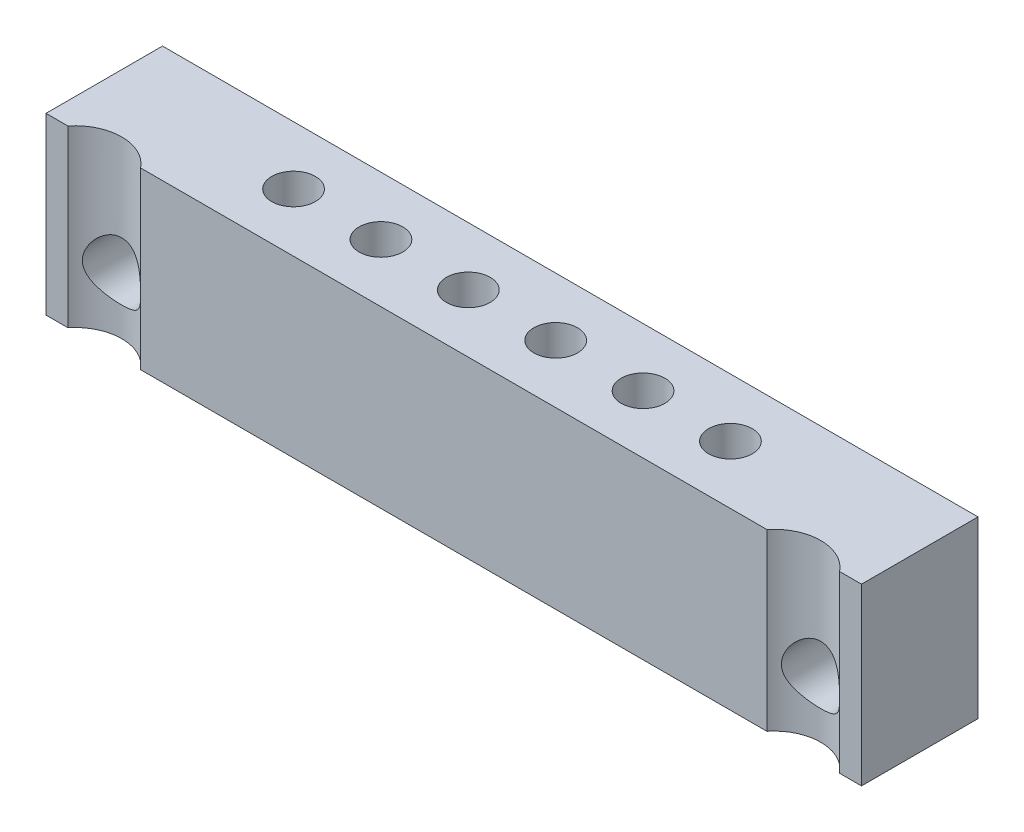
SolidWorks part; units mm, degrees
material "Aleación 1060"
ref_plane "Alzado" through (0, 0, 0) normal (0, 0, 1) x (1, 0, 0)
ref_plane "Planta" through (0, 0, 0) normal (0, 1, 0) x (1, 0, 0)
ref_plane "Vista lateral" through (0, 0, 0) normal (1, 0, 0) x (0, 0, -1)
sketch "Croquis1" plane through (0, 0, 0) normal (0, 0, 1) x (1, 0, 0)
  line L0 (14, 6) -> (14, 0) construction
  line L1 (0, 0) -> (28, 0)
  line L2 (0, 0) -> (0, 6)
  line L3 (0, 6) -> (28, 6)
  line L4 (28, 0) -> (28, 6)
  circle A0 centre (2, 2) radius 1
  circle A1 centre (26, 2) radius 1
  dimension "D3" = 2
  dimension "D5" = 2
  dimension "D1" = 28
  dimension "D2" = 6
  dimension "D4" = 2
extrude "Saliente-Extruir1" add sketch "Croquis1" along normal blind 4
sketch "Croquis2" plane through (0, 0, 0) normal (0, -1, 0) x (1, 0, 0)
  line L0 (0, 4) -> (28, 4) construction
  line L1 (14, 4) -> (14, 0) construction
  line L2 (0, 0) -> (28, 0) construction
  line L3 (9.5, 2) -> (12.5, 2) construction
  circle A0 centre (2, 5) radius 1.6
  circle A1 centre (12.5, 2) radius 0.75
  circle A2 centre (9.5, 2) radius 0.75
  circle A3 centre (6.5, 2) radius 0.75
  circle A4 centre (21.5, 2) radius 0.75
  circle A5 centre (18.5, 2) radius 0.75
  circle A6 centre (15.5, 2) radius 0.75
  circle A7 centre (26, 5) radius 1.6
  dimension "D1" = 1
  dimension "D2" = 2
  dimension "D3" = 1.5
  dimension "D4" = 1.5
  dimension "D5" = 3
extrude "Cortar-Extruir1" cut sketch "Croquis2" against normal up to vertex (6 mm away)
